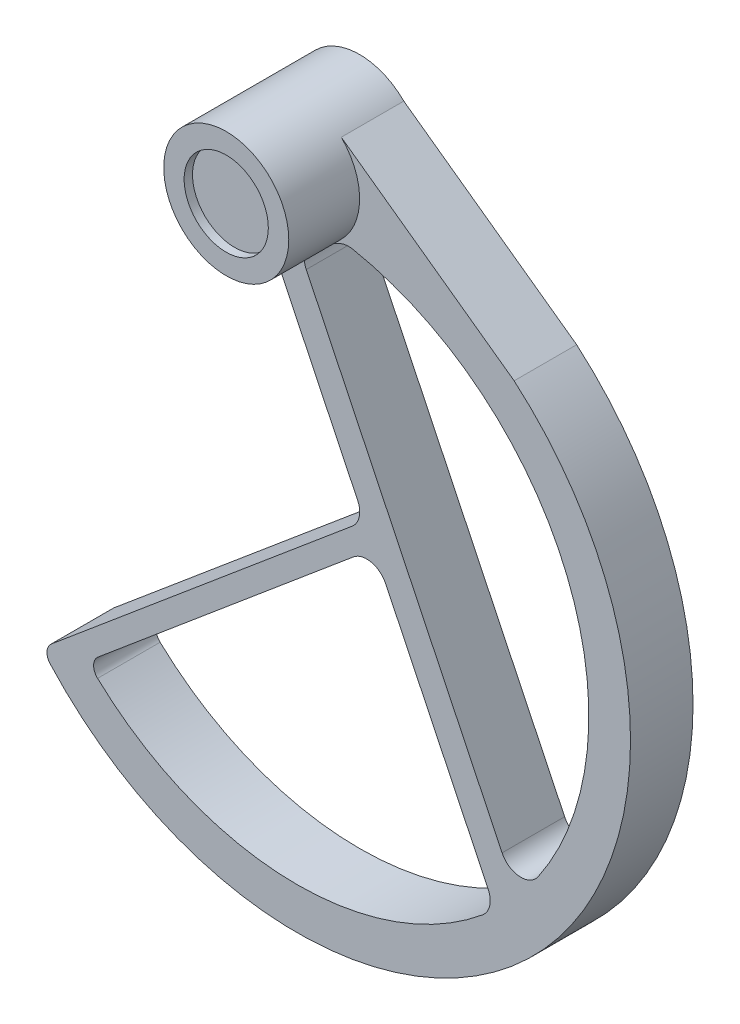
SolidWorks part; units mm, degrees
ref_plane "正面" through (0, 0, 0) normal (0, 0, 1) x (1, 0, 0)
ref_plane "平面" through (0, 0, 0) normal (0, 1, 0) x (1, 0, 0)
ref_plane "右側面" through (0, 0, 0) normal (1, 0, 0) x (0, 0, -1)
sketch "ｽｹｯﾁ4" plane through (0, 0, 0) normal (0, 0, 1) x (1, 0, 0)
  line L0 (0, 0.7897) -> (0, 0)
  line L1 (-53.6231, -124.9951) -> (-58.9406, -129.4571)
  line L3 (-10.6066, -10.6066) -> (14.5363, -62.8896)
  line L4 (-53.6231, -124.9951) -> (13.2442, -68.8868)
  line L5 (21.2324, -76.8138) -> (45.8448, -127.9938)
  line L6 (10.6066, 10.6066) -> (52.0762, -19.2705)
  line L7 (-58.0696, -135.2532) -> (-57.9498, -135.1527)
  line L8 (-47.7477, -126.5866) -> (13.5112, -75.1515)
  arc A1 (-59.2335, -133.7716) -> (52.0762, -19.2705) centre (0, -80) ccw
  arc A2 (-47.8702, -131.073) -> (44.5187, -134.0193) centre (0, -80) ccw
  arc A3 (10.6066, 10.6066) -> (-10.6066, -10.6066) centre (0, 0) ccw
  arc A4 (-59.2335, -133.7716) -> (-58.9406, -129.4571) centre (-57.0123, -131.7552) cw
  arc A5 (-47.8702, -131.073) -> (-47.7477, -126.5866) centre (-45.8186, -128.8841) cw
  arc A6 (13.5112, -75.1515) -> (21.2324, -76.8138) centre (16.7264, -78.9807) cw
  arc A7 (13.2442, -68.8868) -> (14.5363, -62.8896) centre (10.0302, -65.0566) ccw
  arc A8 (45.8448, -127.9938) -> (44.5187, -134.0193) centre (41.3388, -130.1608) cw
  point P18 (-61.2836, -131.423)
  point P21 (-50.2744, -128.7081)
  point P24 (18.4421, -71.0114)
  dimension "D3" = 140
  dimension "D4" = 30
  dimension "D5" = 5
  dimension "D6" = 3
  dimension "D7" = 3
  dimension "D8" = 5
  dimension "D9" = 5
  dimension "D10" = 5
  dimension "D2" = 5
extrude "ﾎﾞｽ - 押し出し1" add sketch "ｽｹｯﾁ4" along normal blind 15
sketch "ｽｹｯﾁ6" plane through (0, 0, 15) normal (0, 0, 1) x (1, 0, 0)
  line L6 (49.1896, -118.7973) -> (2.2018, -21.089)
  line L7 (6.4834, -13.4819) -> (4.5408, -14.416)
  line L8 (6.4834, -13.4819) -> (10.2197, -11.6851)
  arc A0 (57.8261, -119.448) -> (13.3394, -11.2828) centre (0, -80) ccw
  arc A1 (2.2018, -21.089) -> (4.5408, -14.416) centre (6.7078, -18.9221) cw
  arc A2 (13.3394, -11.2828) -> (10.2197, -11.6851) centre (12.3866, -16.1911) ccw
  arc A3 (57.8261, -119.448) -> (49.1896, -118.7973) centre (53.6956, -116.6303) cw
  point P7 (0.0348, -16.583)
  point P14 (52.6925, -126.0814)
  dimension "D3" = 121.502
  dimension "D4" = 70
  dimension "D1" = 5
  dimension "D2" = 5
  dimension "D5" = 5
  dimension "D6" = 90
extrude "ｶｯﾄ - 押し出し1" cut sketch "ｽｹｯﾁ6" against normal blind 15
sketch "ｽｹｯﾁ9" plane through (0, 0, 15) normal (0, 0, 1) x (1, 0, 0)
  circle A0 centre (0, 0) radius 15
extrude "ﾎﾞｽ - 押し出し2" add sketch "ｽｹｯﾁ9" along normal blind 17
sketch "ｽｹｯﾁ10" plane through (0, 0, 32) normal (0, 0, 1) x (1, 0, 0)
  circle A0 centre (0, 0) radius 10.1
extrude "ｶｯﾄ - 押し出し4" cut sketch "ｽｹｯﾁ10" against normal blind 2
